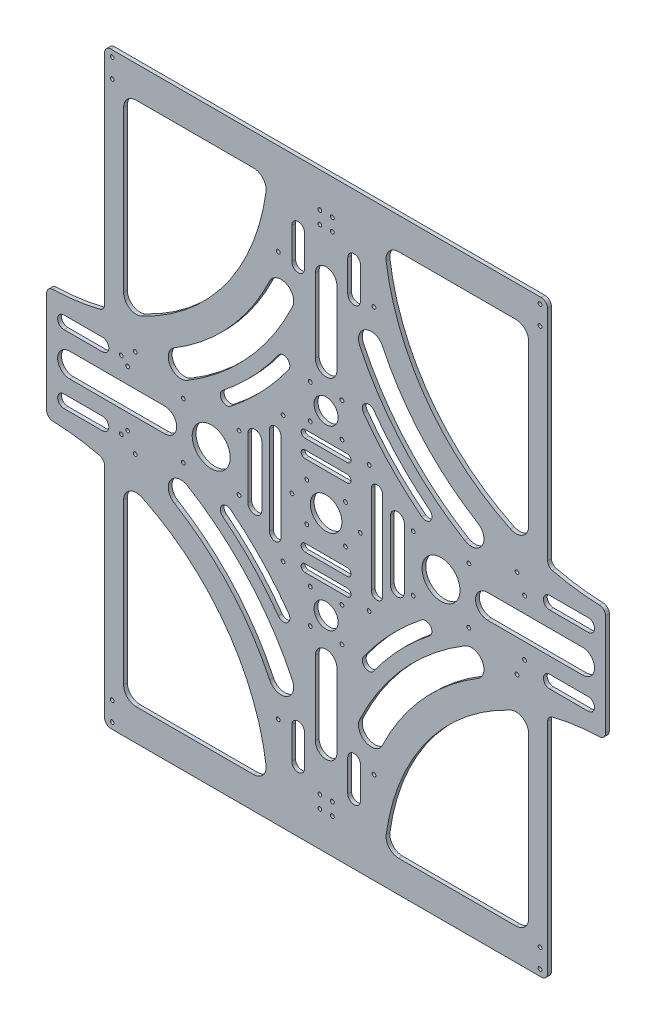
SolidWorks part; units mm, degrees
ref_plane "前视基准面" through (0, 0, 0) normal (0, 0, 1) x (1, 0, 0)
ref_plane "上视基准面" through (0, 0, 0) normal (0, 1, 0) x (1, 0, 0)
ref_plane "右视基准面" through (0, 0, 0) normal (1, 0, 0) x (0, 0, -1)
other "Configuration Table"
sketch "草图1" plane through (0, 0, 0) normal (0, 0, 1) x (1, 0, 0)
  line L0 (-47.9673, 0) -> (67.163, 0) construction
  line L1 (-44.1405, -45) -> (-44.1405, 45)
  line L4 (336.6595, 207.5) -> (222.9065, 207.5)
  line L6 (176.6595, 220) -> (176.6595, 414.0111) construction
  line L7 (397.4595, -45) -> (397.4595, 45)
  line L8 (351.6595, 207.5) -> (351.6595, 232.5)
  line L9 (351.6595, 232.5) -> (1.6595, 232.5)
  line L10 (1.6595, 207.5) -> (1.6595, 232.5)
  line L11 (130.4125, 207.5) -> (16.6595, 207.5)
  line L12 (130.4125, -207.5) -> (16.6595, -207.5)
  line L14 (1.6595, 207.5) -> (1.6595, 51.0996)
  line L16 (16.6595, 207.5) -> (16.6595, 55.9014)
  line L17 (336.6595, 207.5) -> (336.6595, 55.9014)
  line L19 (351.6595, 207.5) -> (351.6595, 51.0996)
  line L21 (336.6595, -207.5) -> (336.6595, -55.9014)
  line L23 (351.6595, -207.5) -> (351.6595, -51.0996)
  line L24 (351.6595, -232.5) -> (1.6595, -232.5)
  line L25 (1.6595, -207.5) -> (1.6595, -232.5)
  line L26 (336.6595, -207.5) -> (222.9065, -207.5)
  line L27 (351.6595, -207.5) -> (351.6595, -232.5)
  line L29 (16.6595, -207.5) -> (16.6595, -55.9014)
  line L31 (1.6595, -207.5) -> (1.6595, -51.0996)
  arc A0 (-44.1405, 45) -> (1.6595, 51.0996) centre (-44.1405, 220) ccw
  arc A1 (397.4595, 45) -> (351.6595, 51.0996) centre (397.4595, 220) cw
  arc A2 (397.4595, -45) -> (351.6595, -51.0996) centre (397.4595, -220) ccw
  arc A3 (-44.1405, -45) -> (1.6595, -51.0996) centre (-44.1405, -220) cw
  arc A4 (16.6595, 55.9014) -> (130.4125, 207.5) centre (-44.1405, 220) ccw
  arc A5 (336.6595, 55.9014) -> (222.9065, 207.5) centre (397.4595, 220) cw
  arc A6 (336.6595, -55.9014) -> (222.9065, -207.5) centre (397.4595, -220) ccw
  arc A7 (16.6595, -55.9014) -> (130.4125, -207.5) centre (-44.1405, -220) cw
  point P7 (397.4595, 0)
  point P19 (-44.1405, 0)
  dimension "D1" = 350
  dimension "D2" = 45
  dimension "D4" = 25
  dimension "D5" = 350
extrude "凸台-拉伸1" add sketch "草图1" along normal blind 3
sketch "草图3" plane through (0, 0, 3) normal (0, 0, 1) x (1, 0, 0)
  line L0 (-44.1405, 0) -> (397.4595, 0) construction
  line L1 (-44.1405, 45) -> (-44.1405, -45) construction
  line L2 (397.4595, -45) -> (397.4595, 45) construction
  line L3 (176.6595, 232.5) -> (176.6595, -232.5) construction
  line L4 (351.6595, 232.5) -> (1.6595, 232.5) construction
  line L5 (1.6595, -232.5) -> (351.6595, -232.5) construction
  line L6 (222.9065, 207.5) -> (222.9065, 232.5) construction
  line L7 (210.6595, -50) -> (142.6595, -50) construction
  line L8 (210.6595, -50) -> (210.6595, 50) construction
  line L9 (210.6595, 50) -> (142.6595, 50) construction
  line L10 (142.6595, -50) -> (142.6595, 50) construction
  line L11 (210.6595, -50) -> (142.6595, 50) construction
  line L12 (210.6595, 50) -> (142.6595, -50) construction
  line L13 (191.9095, -15.25) -> (161.4095, -15.25) construction
  line L14 (191.9095, -15.25) -> (191.9095, 15.25) construction
  line L15 (191.9095, 15.25) -> (161.4095, 15.25) construction
  line L16 (161.4095, -15.25) -> (161.4095, 15.25) construction
  line L17 (191.9095, -15.25) -> (161.4095, 15.25) construction
  line L18 (191.9095, 15.25) -> (161.4095, -15.25) construction
  line L19 (289.4595, -22) -> (245.4595, -22) construction
  line L20 (289.4595, -22) -> (289.4595, 22) construction
  line L21 (289.4595, 22) -> (245.4595, 22) construction
  line L22 (245.4595, -22) -> (245.4595, 22) construction
  line L23 (289.4595, -22) -> (245.4595, 22) construction
  line L24 (289.4595, 22) -> (245.4595, -22) construction
  line L25 (189.1595, 56.5) -> (164.1595, 56.5) construction
  line L26 (189.1595, 56.5) -> (189.1595, 83.5) construction
  line L27 (189.1595, 83.5) -> (164.1595, 83.5) construction
  line L28 (164.1595, 56.5) -> (164.1595, 83.5) construction
  line L29 (189.1595, 56.5) -> (164.1595, 83.5) construction
  line L30 (189.1595, 83.5) -> (164.1595, 56.5) construction
  line L31 (176.6595, 199.9) -> (181.6092, 204.8497) construction
  line L32 (176.6595, 199.9) -> (183.6595, 199.9) construction
  line L33 (7.6595, 232.5) -> (7.6595, 207.5) construction
  line L34 (130.4125, 207.5) -> (16.6595, 207.5) construction
  line L35 (1.6595, 232.5) -> (1.6595, 51.0996) construction
  line L36 (397.4595, 45) -> (245.4595, 45) construction
  line L37 (216.8875, -34.9392) -> (216.8875, 34.9392) construction
  line L43 (159.95, 31.9392) -> (193.369, 31.9392) construction
  line L44 (159.95, 34.9392) -> (193.369, 34.9392)
  line L45 (159.95, 28.9392) -> (193.369, 28.9392)
  line L46 (159.95, 42.9392) -> (193.369, 42.9392)
  line L47 (159.95, 48.9392) -> (193.369, 48.9392)
  line L48 (159.95, 45.9392) -> (193.369, 45.9392) construction
  line L49 (159.95, -31.9392) -> (193.369, -31.9392) construction
  line L50 (159.95, -34.9392) -> (193.369, -34.9392)
  line L51 (159.95, -28.9392) -> (193.369, -28.9392)
  line L52 (159.95, -45.9392) -> (193.369, -45.9392) construction
  line L53 (159.95, -48.9392) -> (193.369, -48.9392)
  line L54 (159.95, -42.9392) -> (193.369, -42.9392)
  line L55 (232.969, 23.6501) -> (232.969, -23.6501) construction
  line L56 (238.4767, 23.6501) -> (238.4767, -23.6501)
  line L57 (227.4614, 23.6501) -> (227.4614, -23.6501)
  line L58 (120.3499, 23.6501) -> (120.3499, -23.6501) construction
  line L59 (114.8423, 23.6501) -> (114.8423, -23.6501)
  line L60 (125.8576, 23.6501) -> (125.8576, -23.6501)
  line L61 (176.6595, 101.6901) -> (176.6595, 160) construction
  line L62 (168.1595, 101.6901) -> (168.1595, 160)
  line L63 (185.1595, 101.6901) -> (185.1595, 160)
  line L64 (176.6595, -101.6901) -> (176.6595, -160) construction
  line L65 (168.1595, -101.6901) -> (168.1595, -160)
  line L66 (185.1595, -101.6901) -> (185.1595, -160)
  line L67 (379.2471, 0) -> (304.2471, 0) construction
  line L68 (379.2471, -9.5) -> (304.2471, -9.5)
  line L69 (379.2471, 9.5) -> (304.2471, 9.5)
  line L70 (-25.9281, 0) -> (49.0719, 0) construction
  line L71 (-25.9281, -9.5) -> (49.0719, -9.5)
  line L72 (-25.9281, 9.5) -> (49.0719, 9.5)
  line L73 (212.3875, -34.9392) -> (212.3875, 34.9392)
  line L74 (221.3875, -34.9392) -> (221.3875, 34.9392)
  line L75 (136.4315, -34.9392) -> (136.4315, 34.9392) construction
  line L76 (140.9315, -34.9392) -> (140.9315, 34.9392)
  line L77 (131.9315, -34.9392) -> (131.9315, 34.9392)
  line L78 (-30.4302, 27) -> (0, 27) construction
  line L79 (-30.4302, 32) -> (0, 32)
  line L80 (-30.4302, 22) -> (0, 22)
  line L81 (-30.4302, -27) -> (0, -27) construction
  line L82 (-30.4302, -32) -> (0, -32)
  line L83 (-30.4302, -22) -> (0, -22)
  line L84 (383.7492, -27) -> (353.319, -27) construction
  line L85 (383.7492, -32) -> (353.319, -32)
  line L86 (383.7492, -22) -> (353.319, -22)
  line L87 (383.7492, 27) -> (353.319, 27) construction
  line L88 (383.7492, 32) -> (353.319, 32)
  line L89 (383.7492, 22) -> (353.319, 22)
  line L90 (154.5588, 158.416) -> (154.5588, 183.4495) construction
  line L93 (149.5588, 158.416) -> (149.5588, 183.4495)
  line L96 (159.5588, 158.416) -> (159.5588, 183.4495)
  line L99 (198.7602, 158.416) -> (198.7602, 183.4495) construction
  line L102 (203.7602, 158.416) -> (203.7602, 183.4495)
  line L103 (193.7602, 158.416) -> (193.7602, 183.4495)
  line L104 (198.7602, -158.416) -> (198.7602, -183.4495) construction
  line L105 (203.7602, -158.416) -> (203.7602, -183.4495)
  line L106 (193.7602, -158.416) -> (193.7602, -183.4495)
  line L107 (154.5588, -158.416) -> (154.5588, -183.4495) construction
  line L108 (149.5588, -158.416) -> (149.5588, -183.4495)
  line L109 (159.5588, -158.416) -> (159.5588, -183.4495)
  circle A0 centre (142.6595, 50) radius 1.5
  circle A1 centre (210.6595, 50) radius 1.5
  circle A2 centre (142.6595, -50) radius 1.5
  circle A3 centre (210.6595, -50) radius 1.5
  circle A4 centre (161.4095, 15.25) radius 1.5
  circle A5 centre (191.9095, 15.25) radius 1.5
  circle A6 centre (191.9095, -15.25) radius 1.5
  circle A7 centre (161.4095, -15.25) radius 1.5
  circle A8 centre (289.4595, 22) radius 1.5
  circle A9 centre (245.4595, 22) radius 1.5
  circle A10 centre (289.4595, -22) radius 1.5
  circle A11 centre (245.4595, -22) radius 1.5
  circle A12 centre (333.4595, 22) radius 1.5
  circle A13 centre (333.4595, -22) radius 1.5
  circle A14 centre (19.8595, -22) radius 1.5
  circle A15 centre (19.8595, 22) radius 1.5
  circle A16 centre (63.8595, 22) radius 1.5
  circle A17 centre (63.8595, -22) radius 1.5
  circle A18 centre (107.8595, -22) radius 1.5
  circle A19 centre (107.8595, 22) radius 1.5
  circle A20 centre (164.1595, 83.5) radius 1.5
  circle A21 centre (189.1595, 83.5) radius 1.5
  circle A22 centre (164.1595, 56.5) radius 1.5
  circle A23 centre (189.1595, 56.5) radius 1.5
  circle A24 centre (164.1595, -56.5) radius 1.5
  circle A25 centre (189.1595, -56.5) radius 1.5
  circle A26 centre (189.1595, -83.5) radius 1.5
  circle A27 centre (164.1595, -83.5) radius 1.5
  circle A30 centre (176.6595, 199.9) radius 7 construction
  circle A31 centre (181.6092, 204.8497) radius 1.5
  circle A32 centre (171.7097, 204.8497) radius 1.5
  circle A33 centre (171.7097, 194.9503) radius 1.5
  circle A34 centre (181.6092, 194.9503) radius 1.5
  circle A35 centre (181.6092, -194.9503) radius 1.5
  circle A36 centre (171.7097, -194.9503) radius 1.5
  circle A37 centre (181.6092, -204.8497) radius 1.5
  circle A38 centre (171.7097, -204.8497) radius 1.5
  circle A39 centre (7.6595, 227.5) radius 1.5
  circle A40 centre (7.6595, 212.5) radius 1.5
  circle A41 centre (345.6595, 212.5) radius 1.5
  circle A42 centre (345.6595, 227.5) radius 1.5
  circle A43 centre (345.6595, -212.5) radius 1.5
  circle A44 centre (345.6595, -227.5) radius 1.5
  circle A45 centre (7.6595, -212.5) radius 1.5
  circle A46 centre (7.6595, -227.5) radius 1.5
  circle A47 centre (214.4595, 160) radius 1.5
  circle A48 centre (138.8595, 160) radius 1.5
  circle A49 centre (214.4595, -160) radius 1.5
  circle A50 centre (138.8595, -160) radius 1.5
  circle A51 centre (327.4595, 35) radius 1.5
  circle A52 centre (327.4595, -35) radius 1.5
  circle A53 centre (25.8595, -35) radius 1.5
  circle A54 centre (25.8595, 35) radius 1.5
  circle A55 centre (14.8595, 27) radius 1.5
  circle A56 centre (14.8595, -27) radius 1.5
  circle A59 centre (176.6595, 0) radius 12.5
  circle A60 centre (176.6595, 70) radius 9.5
  circle A61 centre (176.6595, -70) radius 9.5
  circle A62 centre (267.4595, 0) radius 15
  circle A63 centre (85.8595, 0) radius 15
  arc A64 (61.9559, -44.5903) -> (141.0639, -132.1118) centre (-44.1405, -220) cw construction
  arc A65 (150.0983, -127.8246) -> (67.1313, -36.0338) centre (-44.1405, -220) ccw
  arc A66 (132.0295, -136.3991) -> (56.7805, -53.1469) centre (-44.1405, -220) ccw
  arc A67 (132.0295, -136.3991) -> (150.0983, -127.8246) centre (141.0639, -132.1118) ccw
  arc A68 (67.1313, -36.0338) -> (56.7805, -53.1469) centre (61.9559, -44.5903) ccw
  arc A69 (291.3631, -44.5903) -> (212.2551, -132.1118) centre (397.4595, -220) ccw construction
  arc A70 (203.2207, -127.8246) -> (286.1876, -36.0338) centre (397.4595, -220) cw
  arc A71 (221.2894, -136.3991) -> (296.5385, -53.1469) centre (397.4595, -220) cw
  arc A72 (221.2894, -136.3991) -> (203.2207, -127.8246) centre (212.2551, -132.1118) cw
  arc A73 (286.1876, -36.0338) -> (296.5385, -53.1469) centre (291.3631, -44.5903) cw
  arc A74 (291.3631, 44.5903) -> (212.2551, 132.1118) centre (397.4595, 220) cw construction
  arc A75 (203.2207, 127.8246) -> (286.1876, 36.0338) centre (397.4595, 220) ccw
  arc A76 (221.2894, 136.3991) -> (296.5385, 53.1469) centre (397.4595, 220) ccw
  arc A77 (221.2894, 136.3991) -> (203.2207, 127.8246) centre (212.2551, 132.1118) ccw
  arc A78 (286.1876, 36.0338) -> (296.5385, 53.1469) centre (291.3631, 44.5903) ccw
  arc A79 (61.9559, 44.5903) -> (141.0639, 132.1118) centre (-44.1405, 220) ccw construction
  arc A80 (150.0983, 127.8246) -> (67.1313, 36.0338) centre (-44.1405, 220) cw
  arc A81 (132.0295, 136.3991) -> (56.7805, 53.1469) centre (-44.1405, 220) cw
  arc A82 (132.0295, 136.3991) -> (150.0983, 127.8246) centre (141.0639, 132.1118) cw
  arc A83 (67.1313, 36.0338) -> (56.7805, 53.1469) centre (61.9559, 44.5903) cw
  arc A84 (98.0578, -39.2249) -> (143.0184, -86.3155) centre (-44.1405, -220) cw construction
  arc A85 (147.0871, -83.4093) -> (101.1491, -35.295) centre (-44.1405, -220) ccw
  arc A86 (138.9497, -89.2217) -> (94.9666, -43.1548) centre (-44.1405, -220) ccw
  arc A87 (138.9497, -89.2217) -> (147.0871, -83.4093) centre (143.0184, -86.3155) ccw
  arc A88 (101.1491, -35.295) -> (94.9666, -43.1548) centre (98.0578, -39.2249) ccw
  arc A89 (255.2611, -39.2249) -> (210.3006, -86.3155) centre (397.4595, -220) ccw construction
  arc A90 (206.2319, -83.4093) -> (252.1699, -35.295) centre (397.4595, -220) cw
  arc A91 (214.3693, -89.2217) -> (258.3524, -43.1548) centre (397.4595, -220) cw
  arc A92 (214.3693, -89.2217) -> (206.2319, -83.4093) centre (210.3006, -86.3155) cw
  arc A93 (252.1699, -35.295) -> (258.3524, -43.1548) centre (255.2611, -39.2249) cw
  arc A94 (255.2611, 39.2249) -> (210.3006, 86.3155) centre (397.4595, 220) cw construction
  arc A95 (206.2319, 83.4093) -> (252.1699, 35.295) centre (397.4595, 220) ccw
  arc A96 (214.3693, 89.2217) -> (258.3524, 43.1548) centre (397.4595, 220) ccw
  arc A97 (214.3693, 89.2217) -> (206.2319, 83.4093) centre (210.3006, 86.3155) ccw
  arc A98 (252.1699, 35.295) -> (258.3524, 43.1548) centre (255.2611, 39.2249) ccw
  arc A99 (98.0578, 39.2249) -> (143.0184, 86.3155) centre (-44.1405, 220) ccw construction
  arc A100 (147.0871, 83.4093) -> (101.1491, 35.295) centre (-44.1405, 220) cw
  arc A101 (138.9497, 89.2217) -> (94.9666, 43.1548) centre (-44.1405, 220) cw
  arc A102 (138.9497, 89.2217) -> (147.0871, 83.4093) centre (143.0184, 86.3155) cw
  arc A103 (101.1491, 35.295) -> (94.9666, 43.1548) centre (98.0578, 39.2249) cw
  arc A108 (159.95, 34.9392) -> (159.95, 28.9392) centre (159.95, 31.9392) ccw
  arc A109 (193.369, 28.9392) -> (193.369, 34.9392) centre (193.369, 31.9392) ccw
  arc A110 (159.95, 48.9392) -> (159.95, 42.9392) centre (159.95, 45.9392) ccw
  arc A111 (193.369, 42.9392) -> (193.369, 48.9392) centre (193.369, 45.9392) ccw
  arc A112 (159.95, -34.9392) -> (159.95, -28.9392) centre (159.95, -31.9392) cw
  arc A113 (193.369, -28.9392) -> (193.369, -34.9392) centre (193.369, -31.9392) cw
  arc A114 (159.95, -48.9392) -> (159.95, -42.9392) centre (159.95, -45.9392) cw
  arc A115 (193.369, -42.9392) -> (193.369, -48.9392) centre (193.369, -45.9392) cw
  arc A116 (238.4767, 23.6501) -> (227.4614, 23.6501) centre (232.969, 23.6501) ccw
  arc A117 (227.4614, -23.6501) -> (238.4767, -23.6501) centre (232.969, -23.6501) ccw
  arc A118 (114.8423, 23.6501) -> (125.8576, 23.6501) centre (120.3499, 23.6501) cw
  arc A119 (125.8576, -23.6501) -> (114.8423, -23.6501) centre (120.3499, -23.6501) cw
  arc A120 (168.1595, 101.6901) -> (185.1595, 101.6901) centre (176.6595, 101.6901) ccw
  arc A121 (185.1595, 160) -> (168.1595, 160) centre (176.6595, 160) ccw
  arc A122 (168.1595, -101.6901) -> (185.1595, -101.6901) centre (176.6595, -101.6901) cw
  arc A123 (185.1595, -160) -> (168.1595, -160) centre (176.6595, -160) cw
  arc A124 (379.2471, -9.5) -> (379.2471, 9.5) centre (379.2471, 0) ccw
  arc A125 (304.2471, 9.5) -> (304.2471, -9.5) centre (304.2471, 0) ccw
  arc A126 (-25.9281, -9.5) -> (-25.9281, 9.5) centre (-25.9281, 0) cw
  arc A127 (49.0719, 9.5) -> (49.0719, -9.5) centre (49.0719, 0) cw
  circle A128 centre (149.6595, 0) radius 1.5
  circle A129 centre (203.6595, 0) radius 1.5
  arc A130 (212.3875, -34.9392) -> (221.3875, -34.9392) centre (216.8875, -34.9392) ccw
  arc A131 (221.3875, 34.9392) -> (212.3875, 34.9392) centre (216.8875, 34.9392) ccw
  arc A132 (140.9315, -34.9392) -> (131.9315, -34.9392) centre (136.4315, -34.9392) cw
  arc A133 (131.9315, 34.9392) -> (140.9315, 34.9392) centre (136.4315, 34.9392) cw
  arc A134 (-30.4302, 32) -> (-30.4302, 22) centre (-30.4302, 27) ccw
  arc A135 (0, 22) -> (0, 32) centre (0, 27) ccw
  arc A136 (-30.4302, -32) -> (-30.4302, -22) centre (-30.4302, -27) cw
  arc A137 (0, -22) -> (0, -32) centre (0, -27) cw
  arc A138 (383.7492, -32) -> (383.7492, -22) centre (383.7492, -27) ccw
  arc A139 (353.319, -22) -> (353.319, -32) centre (353.319, -27) ccw
  arc A140 (383.7492, 32) -> (383.7492, 22) centre (383.7492, 27) cw
  arc A141 (353.319, 22) -> (353.319, 32) centre (353.319, 27) cw
  arc A151 (149.5588, 158.416) -> (159.5588, 158.416) centre (154.5588, 158.416) ccw
  arc A152 (159.5588, 183.4495) -> (149.5588, 183.4495) centre (154.5588, 183.4495) ccw
  arc A153 (203.7602, 158.416) -> (193.7602, 158.416) centre (198.7602, 158.416) cw
  arc A154 (193.7602, 183.4495) -> (203.7602, 183.4495) centre (198.7602, 183.4495) cw
  arc A155 (203.7602, -158.416) -> (193.7602, -158.416) centre (198.7602, -158.416) ccw
  arc A156 (193.7602, -183.4495) -> (203.7602, -183.4495) centre (198.7602, -183.4495) ccw
  arc A157 (149.5588, -158.416) -> (159.5588, -158.416) centre (154.5588, -158.416) cw
  arc A158 (159.5588, -183.4495) -> (149.5588, -183.4495) centre (154.5588, -183.4495) cw
  arc A159 (336.6595, -55.9014) -> (222.9065, -207.5) centre (397.4595, -220) ccw construction
  point P12 (176.6595, 0)
  point P21 (176.6595, 0)
  point P30 (267.4595, 0)
  point P55 (176.6595, 70)
  point P89 (176.6595, 199.9)
  point P154 (107.9418, -82.5374)
  point P162 (245.3771, -82.5374)
  point P170 (245.3771, 82.5374)
  point P178 (107.9418, 82.5374)
  point P186 (122.2128, -61.1712)
  point P194 (231.1062, -61.1712)
  point P202 (231.1062, 61.1712)
  point P210 (122.2128, 61.1712)
  point P221 (216.8875, 0)
  point P228 (136.4315, 0)
  point P231 (176.6595, 31.9392)
  point P240 (176.6595, 45.9392)
  point P245 (176.6595, -31.9392)
  point P252 (176.6595, -45.9392)
  point P259 (232.969, 0)
  point P266 (120.3499, 0)
  point P273 (176.6595, 130.8451)
  point P280 (176.6595, -130.8451)
  point P287 (341.7471, 0)
  point P294 (11.5719, 0)
  point P305 (-15.2151, 27)
  point P312 (-15.2151, -27)
  point P319 (368.5341, -27)
  point P326 (368.5341, 27)
  point P332 (154.5588, 170.9327)
  point P333 (200.5512, 181.5069)
  point P340 (152.7677, 181.5069)
  point P342 (198.7602, 170.9327)
  point P347 (200.5512, -181.5069)
  point P350 (198.7602, -170.9327)
  point P354 (152.7677, -181.5069)
  point P358 (154.5588, -170.9327)
  dimension "D3" = 3
  dimension "D4" = 3
  dimension "D5" = 3
  dimension "D6" = 3
  dimension "D9" = 3
  dimension "D10" = 3
  dimension "D11" = 3
  dimension "D12" = 3
  dimension "D16" = 3
  dimension "D17" = 3
  dimension "D18" = 3
  dimension "D19" = 3
  dimension "D20" = 3
  dimension "D22" = 3
  dimension "D27" = 3
  dimension "D28" = 3
  dimension "D29" = 3
  dimension "D30" = 3
  dimension "D31" = 14
  dimension "D34" = 3
  dimension "D37" = 3
  dimension "D39" = 3
  dimension "D41" = 3
  dimension "D44" = 10
  dimension "D46" = 3
  dimension "D47" = 3
  dimension "D50" = 30
  dimension "D51" = 25
  dimension "D52" = 19
  dimension "D53" = 20
  dimension "D54" = 6
  dimension "D56" = 17
  dimension "D58" = 3
  dimension "D62" = 10
  dimension "D64" = 10
  dimension "D65" = 10
  dimension "D66" = 20
  dimension "D1" = 68
  dimension "D2" = 100
  dimension "D7" = 30.5
  dimension "D8" = 30.5
  dimension "D13" = 44
  dimension "D14" = 44
  dimension "D15" = 130
  dimension "D21" = 44
  dimension "D23" = 44
  dimension "D24" = 25
  dimension "D25" = 27
  dimension "D26" = 70
  dimension "D32" = 32.6
  dimension "D33" = 45
  dimension "D36" = 6
  dimension "D38" = 5
  dimension "D40" = 5
  dimension "D42" = 160
  dimension "D43" = 37.8
  dimension "D45" = 150.8
  dimension "D48" = 161.8
  dimension "D49" = 27
  dimension "D57" = 19
  dimension "D59" = 54
  dimension "D60" = 9
  dimension "D61" = 10
  dimension "D63" = 75
  dimension "D55" = 2
  dimension "D35" = 4
extrude "切除-拉伸1" cut sketch "草图3" against normal blind 3
fillet "圆角1" radius 10 12 edges at (336.6595, 55.9014, 1.5) (222.9065, 207.5, 1.5) (336.6595, 207.5, 1.5) (336.6595, -55.9014, 1.5) (222.9065, -207.5, 1.5) (336.6595, -207.5, 1.5) (130.4125, -207.5, 1.5) (16.6595, -207.5, 1.5) (16.6595, -55.9014, 1.5) (16.6595, 55.9014, 1.5) (16.6595, 207.5, 1.5) (130.4125, 207.5, 1.5)
fillet "圆角2" radius 5 8 edges at (351.6595, 232.5, 1.5) (1.6595, 232.5, 1.5) (1.6595, -232.5, 1.5) (351.6595, -232.5, 1.5) (397.4595, -45, 1.5) (397.4595, 45, 1.5) (-44.1405, -45, 1.5) (-44.1405, 45, 1.5)
fillet "圆角3" radius 5 4 edges at (351.6595, -51.0996, 1.5) (351.6595, 51.0996, 1.5) (1.6595, 51.0996, 1.5) (1.6595, -51.0996, 1.5)
